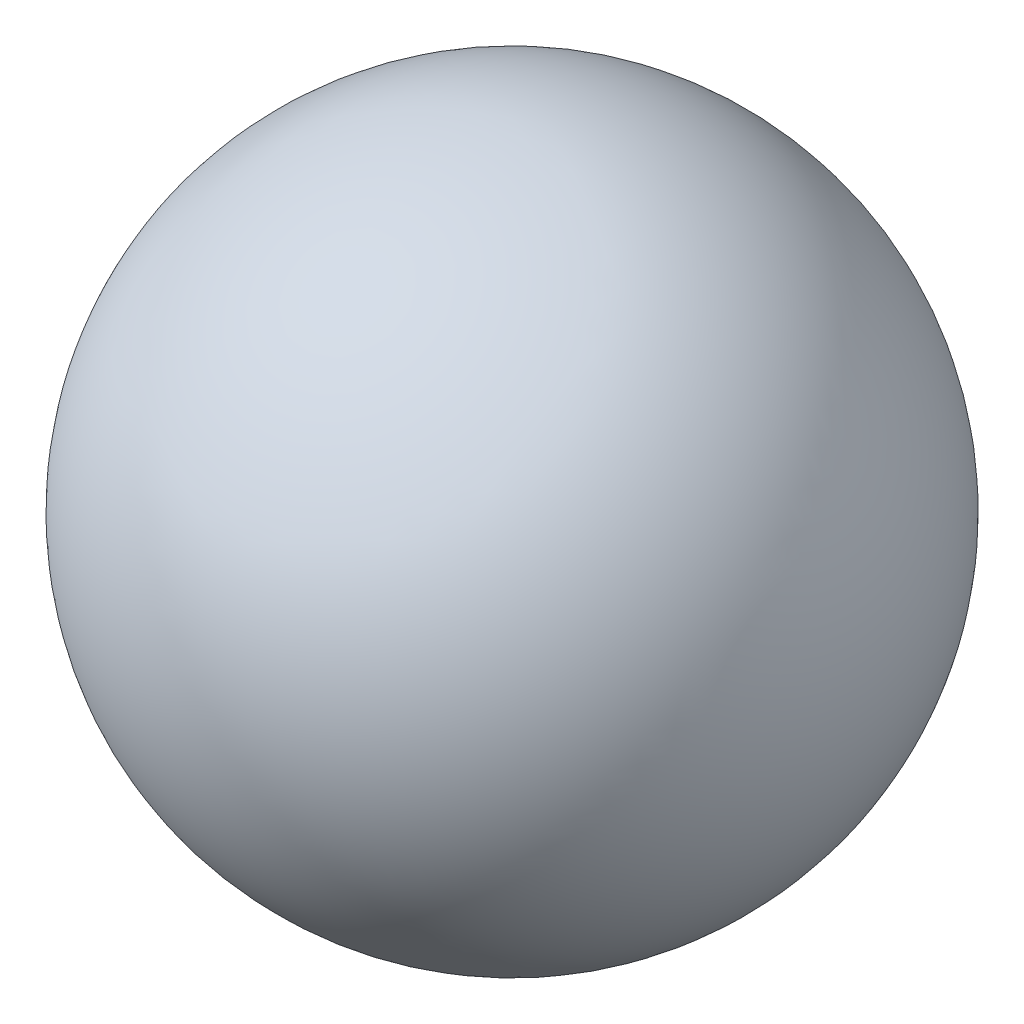
SolidWorks part; units mm, degrees
ref_plane "前视基准面" through (0, 0, 0) normal (0, 0, 1) x (1, 0, 0)
ref_plane "上视基准面" through (0, 0, 0) normal (0, 1, 0) x (1, 0, 0)
ref_plane "右视基准面" through (0, 0, 0) normal (1, 0, 0) x (0, 0, -1)
other "Configuration Table"
sketch "草图1" plane through (0, 0, 0) normal (0, 0, 1) x (1, 0, 0)
  line L0 (0, 0) -> (11, 0) construction
  line L1 (0, 0) -> (-44.9894, 0) construction
  line L2 (11, 0) -> (-11, 0)
  arc A0 (11, 0) -> (-11, 0) centre (0, 0) ccw
  dimension "D1" = 11
revolve "旋转6" add sketch "草图1" angle 360 about L2
